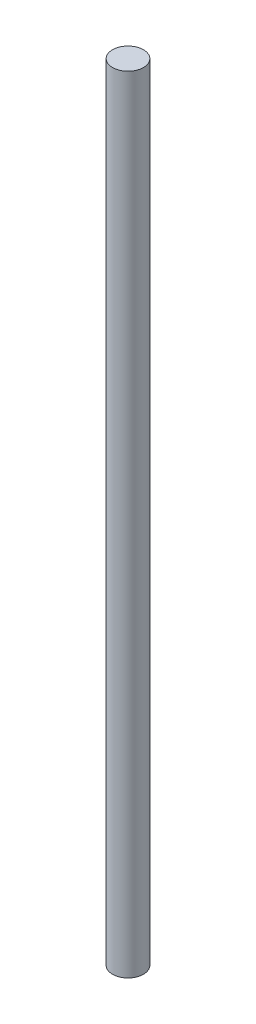
SolidWorks part; units mm, degrees
ref_plane "Front Plane" through (0, 0, 0) normal (0, 0, 1) x (1, 0, 0)
ref_plane "Top Plane" through (0, 0, 0) normal (0, 1, 0) x (1, 0, 0)
ref_plane "Right Plane" through (0, 0, 0) normal (1, 0, 0) x (0, 0, -1)
sketch "Sketch1" plane through (0, 0, 0) normal (0, 1, 0) x (1, 0, 0)
  circle A0 centre (0, 0) radius 5
  dimension "D1" = 10
extrude "Boss-Extrude1" add sketch "Sketch1" along normal blind 254
